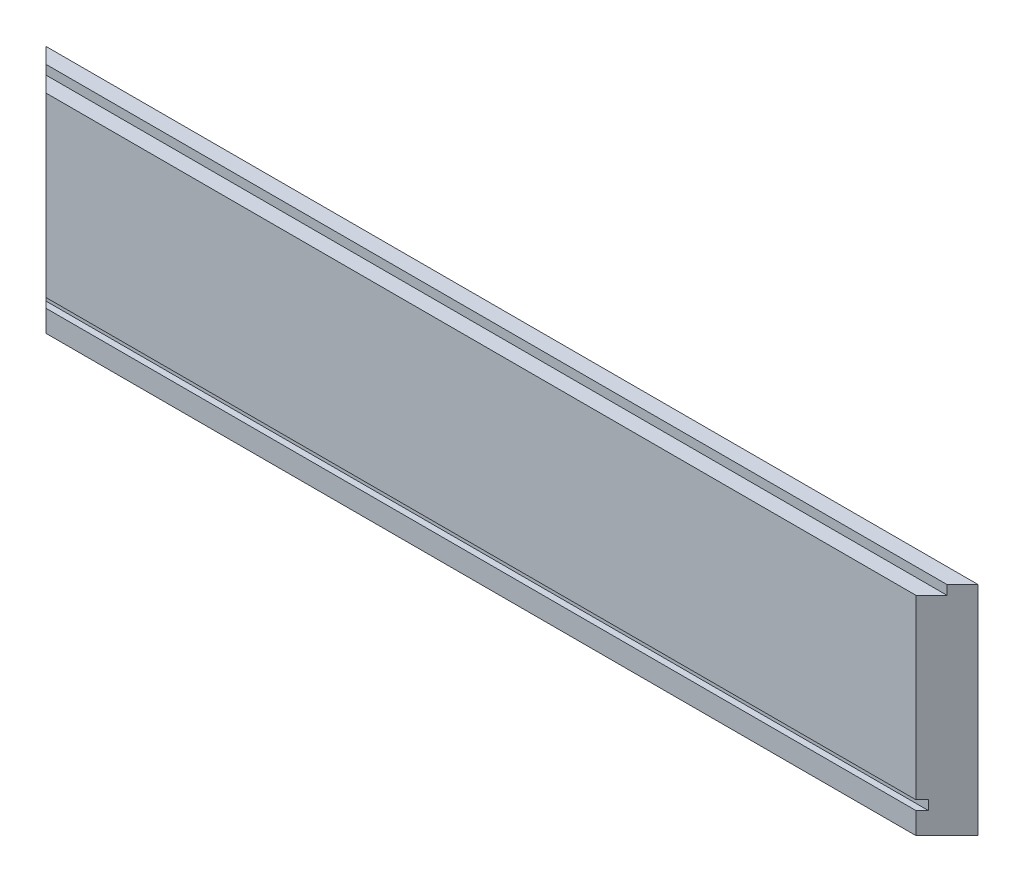
SolidWorks part; units mm, degrees
ref_plane "Front Plane" through (0, 0, 0) normal (0, 0, 1) x (1, 0, 0)
ref_plane "Top Plane" through (0, 0, 0) normal (0, 1, 0) x (1, 0, 0)
ref_plane "Right Plane" through (0, 0, 0) normal (1, 0, 0) x (0, 0, -1)
sketch "Sketch1" plane through (0, 0, 0) normal (0, 1, 0) x (1, 0, 0)
  line L1 (0, 0) -> (300, 0)
  line L2 (0, 0) -> (0, 10)
  line L3 (0, 10) -> (300, 10)
  line L4 (300, 0) -> (300, 10)
  line L5 (10, 0) -> (0, 10)
  line L6 (300, 10) -> (290, 0)
  dimension "D1" = 10
  dimension "D2" = 300
  dimension "D3" = 10
  dimension "D4" = 10
extrude "Boss-Extrude1" add sketch "Sketch1" along normal blind 70 contours L6 L3 L5 L1
sketch "Sketch2" plane through (0, 70, 0) normal (0, 1, 0) x (1, 0, 0)
  line L0 (5, 5) -> (295, 5)
  line L1 (10, 0) -> (0, 10) construction
  line L2 (300, 10) -> (290, 0) construction
  line M2 (290, 0) -> (300, 10)
  line M4 (0, 10) -> (10, 0)
  line M5 (10, 0) -> (290, 0)
extrude "Cut-Extrude1" cut sketch "Sketch2" against normal blind 3 and the other way through all contours L0 M4 M5 M2
sketch "Sketch3" plane through (0, 0, 0) normal (0, 0, 1) x (1, 0, 0)
  line L0 (0, 70) -> (0, 0) construction
  line L1 (0, 7) -> (300, 7)
  line L2 (0, 7) -> (0, 10)
  line L3 (0, 10) -> (300, 10)
  line L4 (300, 7) -> (300, 10)
  line L5 (300, 70) -> (300, 0) construction
  line L6 (10, 0) -> (290, 0) construction
  dimension "D1" = 10
  dimension "D2" = 7
extrude "Cut-Extrude2" cut sketch "Sketch3" against normal blind 2
